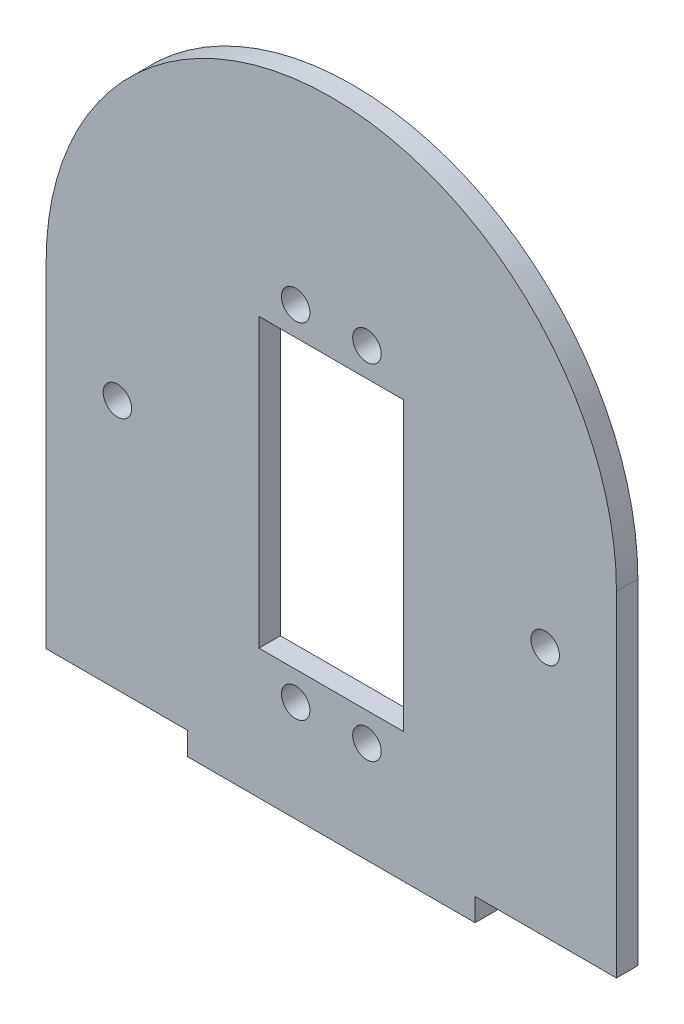
SolidWorks part; units mm, degrees
ref_plane "Front Plane" through (0, 0, 0) normal (0, 0, 1) x (1, 0, 0)
ref_plane "Top Plane" through (0, 0, 0) normal (0, 1, 0) x (1, 0, 0)
ref_plane "Right Plane" through (0, 0, 0) normal (1, 0, 0) x (0, 0, -1)
sketch "Croquis1" plane through (0, 0, 0) normal (0, 0, 1) x (1, 0, 0)
  line L3 (-20.175, -47) -> (20.175, -47) construction
  line L4 (40, 0) -> (40, -47)
  line L6 (0, 0) -> (28.2843, 28.2843) construction
  line L14 (0, 0) -> (40, 0) construction
  line L20 (0, 0) -> (0, -47) construction
  line L21 (-28.2843, 28.2843) -> (0, 0) construction
  line L23 (-20.175, -47) -> (-20.175, -50.2)
  line L25 (20.175, -50.2) -> (20.175, -47)
  line L26 (0, -50.2) -> (0, -47) construction
  line L27 (-40, 0) -> (-40, -47)
  line L28 (-40, -47) -> (-20.175, -47)
  line L29 (20.175, -47) -> (40, -47)
  line L30 (0, -11.85) -> (10.15, -11.85) construction
  line L31 (-10.15, 8.3) -> (10.15, 8.3)
  line L32 (-10.15, 8.3) -> (-10.15, -32)
  line L33 (-10.15, -32) -> (10.15, -32)
  line L34 (10.15, 8.3) -> (10.15, -32)
  line L35 (-10.15, 8.3) -> (10.15, -32) construction
  line L36 (-10.15, -32) -> (10.15, 8.3) construction
  line L39 (-20.175, -50.2) -> (20.175, -50.2) construction
  line L40 (-20.175, -50.2) -> (20.175, -50.2)
  arc A12 (-40, 0) -> (0, 40) centre (0, 0) cw
  arc A13 (40, 0) -> (0, 40) centre (0, 0) ccw
  circle A14 centre (-5, 12.3) radius 2
  circle A15 centre (5, 12.3) radius 2
  circle A16 centre (5, -36) radius 2
  circle A17 centre (-5, -36) radius 2
  circle A19 centre (-30, -11.85) radius 2
  circle A20 centre (30, -11.85) radius 2
  point P0 (0, 0)
  point P4 (0, -11.85)
  point P37 (0, -51.5)
  dimension "D3" = 4.5
  dimension "D4" = 80
  dimension "D5" = 45
  dimension "D6" = 45
  dimension "D14" = 4
  dimension "D10" = 4
  dimension "D18" = 4
  dimension "D2" = 87
  dimension "D7" = 20.3
  dimension "D8" = 40.3
  dimension "D9" = 15
  dimension "D11" = 40.35
  dimension "D13" = 10
  dimension "D15" = 3.2
  dimension "D19" = 35.15
  dimension "D20" = 30
extrude "Saliente-Extruir1" add sketch "Croquis1" along normal blind 3
